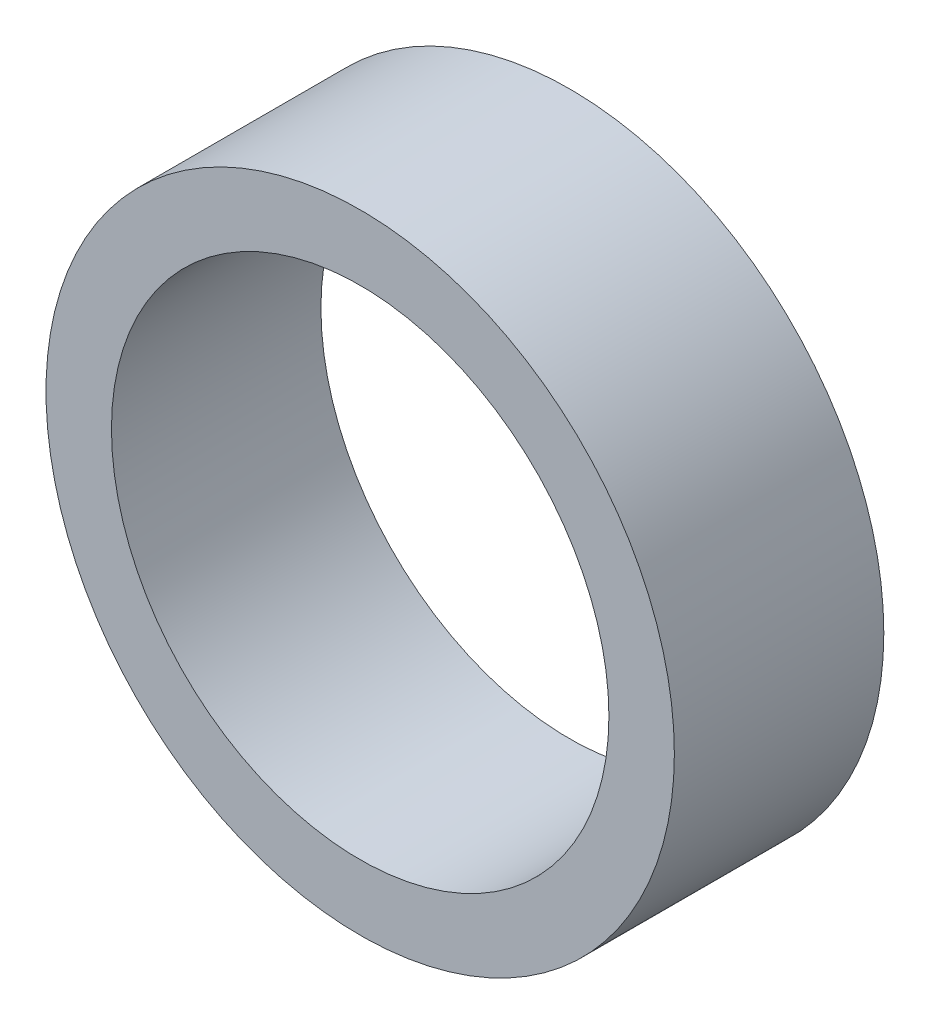
SolidWorks part; units mm, degrees
material "6061 Alloy"
ref_plane "Front Plane" through (0, 0, 0) normal (0, 0, 1) x (1, 0, 0)
ref_plane "Top Plane" through (0, 0, 0) normal (0, 1, 0) x (1, 0, 0)
ref_plane "Right Plane" through (0, 0, 0) normal (1, 0, 0) x (0, 0, -1)
sketch "Sketch1" plane through (0, 0, 0) normal (0, 0, 1) x (1, 0, 0)
  circle A0 centre (0, 0) radius 7.5406
  circle A1 centre (0, 0) radius 9.525
  dimension "D1" = 19.05
  dimension "19/32" = 15.0812
extrude "Boss-Extrude1" add sketch "Sketch1" along normal mid plane 6.35
